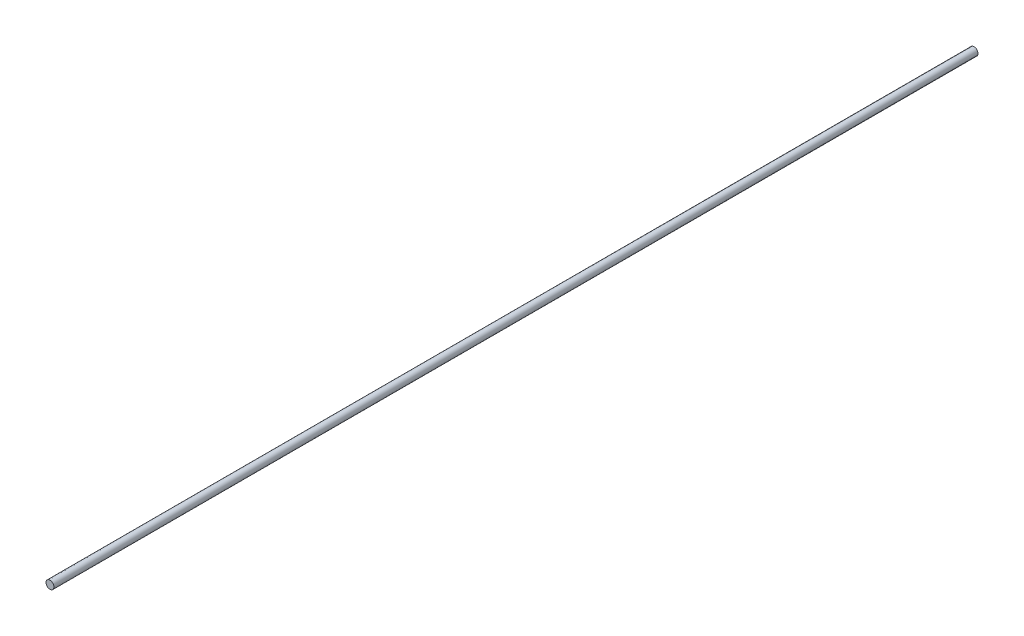
SolidWorks part; units mm, degrees
ref_plane "Спереди" through (0, 0, 0) normal (0, 0, 1) x (1, 0, 0)
ref_plane "Сверху" through (0, 0, 0) normal (0, 1, 0) x (1, 0, 0)
ref_plane "Справа" through (0, 0, 0) normal (1, 0, 0) x (0, 0, -1)
sketch "Эскиз1" plane through (0, 0, 0) normal (0, 0, 1) x (-1, 0, 0)
  circle A0 centre (-6.5, 15.25) radius 2.9995
extrude "Бобышка-Вытянуть1" add sketch "Эскиз1" along normal blind 700 contours A0
